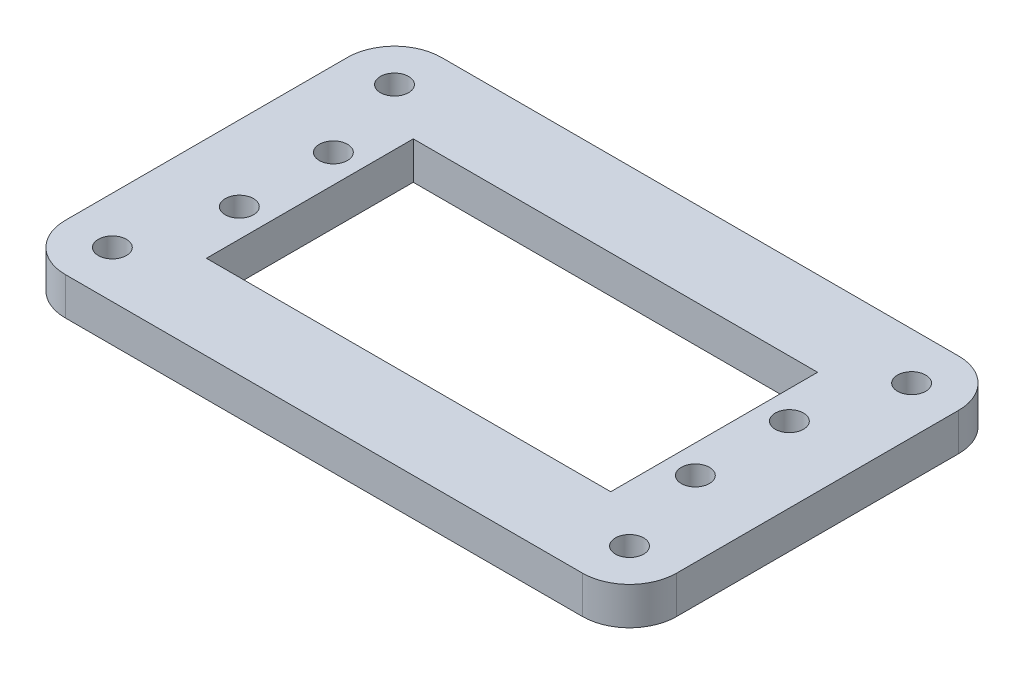
SolidWorks part; units mm, degrees
ref_plane "Front Plane" through (0, 0, 0) normal (0, 0, 1) x (1, 0, 0)
ref_plane "Top Plane" through (0, 0, 0) normal (0, 1, 0) x (1, 0, 0)
ref_plane "Right Plane" through (0, 0, 0) normal (1, 0, 0) x (0, 0, -1)
sketch "Sketch1" plane through (0, 0, 0) normal (0, 1, 0) x (1, 0, 0)
  line L1 (-32.5, 20) -> (32.5, 20)
  line L2 (-32.5, 20) -> (-32.5, -20)
  line L3 (-32.5, -20) -> (32.5, -20)
  line L4 (32.5, 20) -> (32.5, -20)
  line L5 (-32.5, 20) -> (32.5, -20) construction
  line L6 (-32.5, -20) -> (32.5, 20) construction
  line L7 (-21.5, 11) -> (21.5, 11)
  line L8 (-21.5, 11) -> (-21.5, -11)
  line L9 (-21.5, -11) -> (21.5, -11)
  line L10 (21.5, 11) -> (21.5, -11)
  line L11 (-21.5, 11) -> (21.5, -11) construction
  line L12 (-21.5, -11) -> (21.5, 11) construction
  point P0 (0, 0)
  point P6 (0, 0)
  dimension "D1" = 40
  dimension "D2" = 65
  dimension "D3" = 22
  dimension "D4" = 43
extrude "Boss-Extrude1" add sketch "Sketch1" along normal blind 4
sketch "Sketch2" plane through (0, 4, 0) normal (0, 1, 0) x (1, 0, 0)
  line L0 (-21.5, 11) -> (-21.5, -11) construction
  line L1 (21.5, -11) -> (21.5, 11) construction
  line L2 (32.5, 20) -> (-32.5, 20) construction
  line L3 (-32.5, 20) -> (-32.5, -20) construction
  line L4 (32.5, -20) -> (32.5, 20) construction
  line L5 (-32.5, -20) -> (32.5, -20) construction
  circle A0 centre (-24.5, 5.5045) radius 1.5
  circle A1 centre (-24.5, -4.4955) radius 1.5
  circle A2 centre (24.5, 5) radius 1.5
  circle A3 centre (24.5, -5) radius 1.5
  circle A4 centre (-27.5, 15) radius 1.5
  circle A5 centre (27.5, 15) radius 1.5
  circle A6 centre (27.5, -15) radius 1.5
  circle A7 centre (-27.5, -15) radius 1.5
  point P0 (24.5, 0)
  point P1 (24.5, 5)
  point P2 (-24.5, 0.5045)
  point P3 (-24.5, 5.5045)
  point P4 (-24.5, -4.4955)
  point P5 (24.5, -5)
  point P18 (-27.5, 15)
  point P21 (27.5, 15)
  point P26 (27.5, -15)
  point P29 (-27.5, -15)
  dimension "D7" = 3
  dimension "D8" = 3
  dimension "D9" = 3
  dimension "D10" = 3
  dimension "D15" = 3
  dimension "D16" = 3
  dimension "D17" = 3
  dimension "D18" = 3
  dimension "D1" = 5
  dimension "D2" = 5
  dimension "D3" = 5
  dimension "D4" = 3
  dimension "D5" = 3
  dimension "D6" = 5
  dimension "D11" = 5
  dimension "D12" = 5
  dimension "D13" = 5
  dimension "D14" = 5
extrude "Cut-Extrude1" cut sketch "Sketch2" against normal through all
fillet "Fillet1" radius 5 1 edges at (-32.5, 2, -20)
fillet "Fillet2" radius 5 1 edges at (32.5, 2, -20)
fillet "Fillet3" radius 5 1 edges at (32.5, 2, 20)
fillet "Fillet4" radius 5 1 edges at (-32.5, 2, 20)
